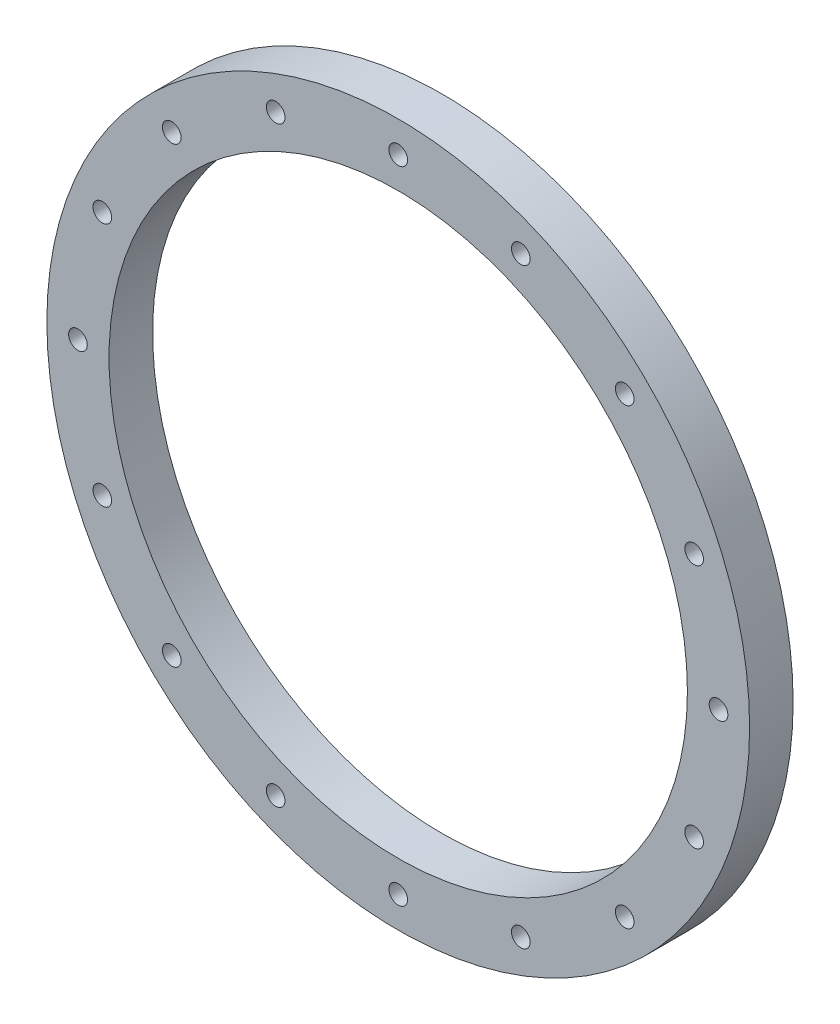
SolidWorks part; units mm, degrees
material "Stainless Steel 2205"
ref_plane "Front Plane" through (0, 0, 0) normal (0, 0, 1) x (1, 0, 0)
ref_plane "Top Plane" through (0, 0, 0) normal (0, 1, 0) x (1, 0, 0)
ref_plane "Right Plane" through (0, 0, 0) normal (1, 0, 0) x (0, 0, -1)
sketch "Sketch1" plane through (0, 0, 0) normal (0, 0, 1) x (1, 0, 0)
  circle A0 centre (0, 0) radius 464.965
  circle A1 centre (0, 0) radius 564.965
  dimension "D1" = 1129.93
  dimension "D2" = 100
extrude "Boss-Extrude1" add sketch "Sketch1" along normal blind 70
sketch "Sketch3" plane through (0, 0, 70) normal (0, 0, 1) x (1, 0, 0)
  line L0 (0, 0) -> (0, 514.965) construction
  line L1 (197.0686, 475.7656) -> (0, 0) construction
  circle A0 centre (0, 0) radius 514.965 construction
  circle A1 centre (0, 0) radius 564.965 construction
  circle A2 centre (197.0686, 475.7656) radius 15
  circle A3 centre (364.1352, 364.1352) radius 15
  circle A4 centre (475.7656, 197.0686) radius 15
  circle A5 centre (514.965, 0) radius 15
  circle A6 centre (475.7656, -197.0686) radius 15
  circle A7 centre (364.1352, -364.1352) radius 15
  circle A8 centre (197.0686, -475.7656) radius 15
  circle A9 centre (0, -514.965) radius 15
  circle A10 centre (-197.0686, -475.7656) radius 15
  circle A11 centre (-364.1352, -364.1352) radius 15
  circle A12 centre (-475.7656, -197.0686) radius 15
  circle A13 centre (-514.965, 0) radius 15
  circle A14 centre (-475.7656, 197.0686) radius 15
  circle A15 centre (-364.1352, 364.1352) radius 15
  circle A16 centre (-197.0686, 475.7656) radius 15
  circle A17 centre (0, 514.965) radius 15
  point P41 (0, 0)
  dimension "D1" = 50
  dimension "D2" = 30
  dimension "D3" = 22.5
  dimension "D4" = 16
extrude "Cut-Extrude2" cut sketch "Sketch3" against normal through all both and the other way through all
equation "\"hatchHoleDiameter\"=600mm"
equation "\"hullThickness\"=177.1mm"
equation "\"gasketHullInterconnectWidth\"=100mm"
equation "\"collarThickness\"=20mm"
equation "\"hatchTunnelLength\"=200mm"
equation "\"oRingDiameter\"=2mm"
equation "\"boltPatternRadiusInterconnect\"=500mm"
equation "\"interconnectBoltDiameter\"=30mm"
equation "\"hatchShaftDiameter\"=20mm"
equation "\"hatchMinima\"=39.9mm"
equation "\"hullDiameter\"=2240mm"
equation "\"hatchMaxima\"=180mm"
equation "\"bushingFlatHatch\"=15mm"
equation "\"hingePivotDiameter\"=20mm"
equation "\"handleWidth\"=250mm"
equation "\"handleHeight\"=160mm"
equation "\"handleThickness\"=25mm"
equation "\"FrameLength\"=2600mm"
equation "\"FrameMidLength\"=1800mm"
equation "\"TubeOD\"=100mm"
equation "\"FrameBackFlat\"=500mm"
equation "\"TubeWall\"=15.0001mm"
equation "\"TopMemberAngle\"=140deg"
equation "\"FrameHight\"=2500mm"
